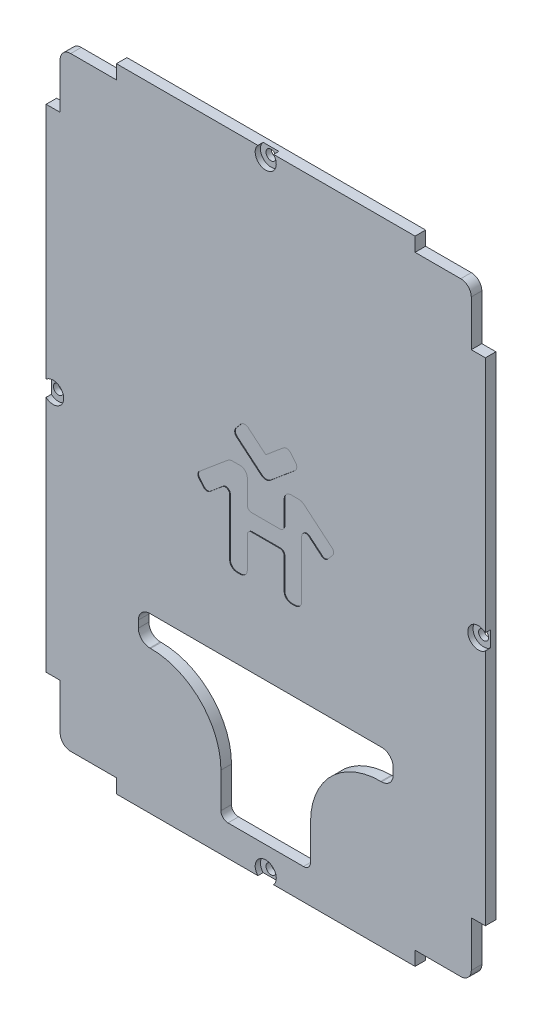
SolidWorks part; units mm, degrees
ref_plane "Спереди" through (0, 0, 0) normal (0, 0, 1) x (1, 0, 0)
ref_plane "Сверху" through (0, 0, 0) normal (0, 1, 0) x (1, 0, 0)
ref_plane "Справа" through (0, 0, 0) normal (1, 0, 0) x (0, 0, -1)
sketch "Эскиз1" plane through (0, 0, 0) normal (0, 0, 1) x (1, 0, 0)
  line L1 (-52.5, -90) -> (52.5, -90)
  line L2 (-62.5, -80) -> (-62.5, 80)
  line L3 (-52.5, 90) -> (52.5, 90)
  line L4 (62.5, -80) -> (62.5, 80)
  line L5 (-62.5, -90) -> (62.5, 90) construction
  line L6 (-62.5, 90) -> (62.5, -90) construction
  arc A0 (-52.5, 90) -> (-62.5, 80) centre (-52.5, 80) ccw
  arc A1 (-52.5, -90) -> (-62.5, -80) centre (-52.5, -80) cw
  arc A2 (52.5, 90) -> (62.5, 80) centre (52.5, 80) cw
  arc A3 (62.5, -80) -> (52.5, -90) centre (52.5, -80) cw
  point P0 (0, 0)
  dimension "D3" = 10
  dimension "D4" = 10
  dimension "D1" = 125
  dimension "D2" = 180
extrude "Бобышка-Вытянуть1" add sketch "Эскиз1" along normal blind 3
sketch "Эскиз2" plane through (0, 0, 0) normal (0, 0, -1) x (-1, 0, 0)
  line L0 (-36.25, -44) -> (-36.25, -46)
  line L1 (-33, -49.25) -> (-32.75, -49.25)
  line L2 (-12.75, -69.25) -> (-12.75, -79.25)
  line L3 (-10.75, -81.25) -> (10.75, -81.25)
  line L4 (12.75, -79.25) -> (12.75, -69.25)
  line L5 (32.75, -49.25) -> (33, -49.25)
  line L6 (36.25, -46) -> (36.25, -44)
  line L7 (33, -40.75) -> (-33, -40.75)
  line L8 (-62.5, -80) -> (-62.5, 80) construction
  line L9 (62.5, 80) -> (62.5, -80) construction
  line L10 (52.5, -90) -> (-52.5, -90) construction
  arc A0 (32.75, -49.25) -> (12.75, -69.25) centre (32.75, -69.25) ccw
  arc A1 (-12.75, -69.25) -> (-32.75, -49.25) centre (-32.75, -69.25) ccw
  arc A2 (33, -49.25) -> (36.25, -46) centre (33, -46) ccw
  arc A3 (36.25, -44) -> (33, -40.75) centre (33, -44) ccw
  arc A4 (-33, -49.25) -> (-36.25, -46) centre (-33, -46) cw
  arc A5 (-33, -40.75) -> (-36.25, -44) centre (-33, -44) ccw
  arc A6 (12.75, -79.25) -> (10.75, -81.25) centre (10.75, -79.25) cw
  arc A7 (-10.75, -81.25) -> (-12.75, -79.25) centre (-10.75, -79.25) cw
  point P16 (12.75, -49.25)
  point P21 (36.25, -49.25)
  point P24 (36.25, -40.75)
  point P31 (12.75, -81.25)
  point P34 (-12.75, -81.25)
  dimension "D7" = 20
  dimension "D8" = 3.25
  dimension "D9" = 2
  dimension "D1" = 26.25
  dimension "D2" = 26.25
  dimension "D3" = 49.25
  dimension "D4" = 8.5
  dimension "D5" = 25.5
  dimension "D6" = 32
extrude "Вырез-Вытянуть1" cut sketch "Эскиз2" against normal blind 10
sketch "Эскиз3" plane through (0, 0, 3) normal (0, 0, 1) x (1, 0, 0)
  line L0 (-60.5, -940.9285) -> (-60.5, 49059.0715) construction
  line L1 (60.5, -944.6511) -> (60.5, 49055.3489) construction
  line L2 (-1032.3277, 88) -> (48967.6723, 88) construction
  line L3 (-1028.801, -88) -> (48971.199, -88) construction
  line L4 (-52.5, -90) -> (52.5, -90) construction
  line L6 (-62.5, 80) -> (-62.5, -80) construction
  line L7 (62.5, -80) -> (62.5, 80) construction
  line L8 (52.5, 90) -> (-52.5, 90) construction
  line L9 (0, -925) -> (0, 49075) construction
  line L10 (-1052.5, 0) -> (48947.5, 0) construction
  circle A1 centre (0, 88) radius 3
  circle A3 centre (60.5, 0) radius 3
  circle A5 centre (0, -88) radius 3
  circle A7 centre (-60.5, 0) radius 3
  point P19 (0, 90)
  point P22 (-62.5, 0)
  dimension "D5" = 6
  dimension "D1" = 2
  dimension "D2" = 2
  dimension "D3" = 2
  dimension "D4" = 2
extrude "Вырез-Вытянуть2" cut sketch "Эскиз3" against normal blind 1.5
sketch "Эскиз4" plane through (0, 0, 1.5) normal (0, 0, 1) x (1, 0, 0)
  circle A1 centre (0, 88) radius 1.425
  circle A3 centre (60.5, 0) radius 1.425
  circle A5 centre (0, -88) radius 1.425
  circle A7 centre (-60.5, 0) radius 1.425
  dimension "D1" = 2.85
extrude "Вырез-Вытянуть3" cut sketch "Эскиз4" against normal blind 2
sketch "Эскиз5" plane through (0, 0, 3) normal (0, 0, 1) x (1, 0, 0)
  line L0 (-10.25, -0.0911) -> (-10.25, -16.2185)
  line L1 (-8.25, -18.2185) -> (-7.25, -18.2185)
  line L2 (-5.25, -16.2185) -> (-5.25, -7.4685)
  line L3 (-4, -6.2185) -> (4, -6.2185)
  line L4 (-9.3401, 8.5815) -> (-7.25, 8.5815)
  line L5 (-5.25, 6.5815) -> (-5.25, -0.1685)
  line L6 (0, -1000.6685) -> (0, 48999.3315) construction
  line L7 (-4, -1.4185) -> (4, -1.4185)
  line L8 (-10.947, 7.9966) -> (-18.868, 1.3501)
  line L9 (-19.0221, -0.4109) -> (-17.6786, -2.012)
  line L10 (-15.9176, -2.1661) -> (-12.3035, 0.8665)
  line L11 (15.9176, -2.1661) -> (12.3035, 0.8665)
  line L12 (19.0221, -0.4109) -> (17.6786, -2.012)
  line L13 (10.947, 7.9966) -> (18.868, 1.3501)
  line L14 (5.25, 6.5815) -> (5.25, -0.1685)
  line L15 (9.3401, 8.5815) -> (7.25, 8.5815)
  line L16 (5.25, -16.2185) -> (5.25, -7.4685)
  line L17 (8.25, -18.2185) -> (7.25, -18.2185)
  line L18 (10.25, -0.0911) -> (10.25, -16.2185)
  line L19 (0, 14.8585) -> (-4.9795, 19.0368)
  line L20 (-7.0927, 18.8519) -> (-8.4839, 17.194)
  line L21 (-8.299, 15.0808) -> (-1.2856, 9.1958)
  line L22 (8.299, 15.0808) -> (1.2856, 9.1958)
  line L23 (0, 14.8585) -> (4.9795, 19.0368)
  line L24 (7.0927, 18.8519) -> (8.4839, 17.194)
  arc A0 (-10.25, -16.2185) -> (-8.25, -18.2185) centre (-8.25, -16.2185) ccw
  arc A1 (-7.25, -18.2185) -> (-5.25, -16.2185) centre (-7.25, -16.2185) ccw
  arc A2 (-5.25, 6.5815) -> (-7.25, 8.5815) centre (-7.25, 6.5815) ccw
  arc A3 (-9.3401, 8.5815) -> (-10.947, 7.9966) centre (-9.3401, 6.0815) ccw
  arc A4 (-4, -6.2185) -> (-5.25, -7.4685) centre (-4, -7.4685) ccw
  arc A5 (-4, -1.4185) -> (-5.25, -0.1685) centre (-4, -0.1685) cw
  arc A6 (-10.25, -0.0911) -> (-12.3035, 0.8665) centre (-11.5, -0.0911) ccw
  arc A7 (-15.9176, -2.1661) -> (-17.6786, -2.012) centre (-16.721, -1.2085) cw
  arc A8 (-18.868, 1.3501) -> (-19.0221, -0.4109) centre (-18.0645, 0.3926) ccw
  arc A9 (18.868, 1.3501) -> (19.0221, -0.4109) centre (18.0645, 0.3926) cw
  arc A10 (15.9176, -2.1661) -> (17.6786, -2.012) centre (16.721, -1.2085) ccw
  arc A11 (10.25, -0.0911) -> (12.3035, 0.8665) centre (11.5, -0.0911) cw
  arc A12 (4, -1.4185) -> (5.25, -0.1685) centre (4, -0.1685) ccw
  arc A13 (4, -6.2185) -> (5.25, -7.4685) centre (4, -7.4685) cw
  arc A14 (9.3401, 8.5815) -> (10.947, 7.9966) centre (9.3401, 6.0815) cw
  arc A15 (5.25, 6.5815) -> (7.25, 8.5815) centre (7.25, 6.5815) cw
  arc A16 (7.25, -18.2185) -> (5.25, -16.2185) centre (7.25, -16.2185) cw
  arc A17 (10.25, -16.2185) -> (8.25, -18.2185) centre (8.25, -16.2185) cw
  arc A18 (-8.299, 15.0808) -> (-8.4839, 17.194) centre (-7.3348, 16.2298) cw
  arc A19 (-4.9795, 19.0368) -> (-7.0927, 18.8519) centre (-5.9437, 17.8877) ccw
  arc A20 (4.9795, 19.0368) -> (7.0927, 18.8519) centre (5.9437, 17.8877) cw
  arc A21 (8.299, 15.0808) -> (8.4839, 17.194) centre (7.3348, 16.2298) ccw
  arc A22 (1.2856, 9.1958) -> (-1.2856, 9.1958) centre (0, 10.7279) cw
  point P35 (0, -6.2185)
  point P36 (0, -1.4185)
  point P61 (19.57, 0.5466)
  point P62 (4.9945, -1.4185)
  point P63 (4.9945, -6.2185)
  point P64 (9.9945, 8.5815)
  point P65 (4.9945, 8.5815)
  point P66 (4.9945, -18.2185)
  point P67 (9.9945, -18.2185)
  point P79 (5.7231, 19.8752)
  point P80 (8.937, 16.0449)
  dimension "D3" = 2
  dimension "D4" = 2.5
  dimension "D6" = 1.5
  dimension "D7" = 2
  dimension "D8" = 1.25
  dimension "D1" = 5.25
  dimension "D2" = 50
  dimension "D5" = 50
extrude "Вырез-Вытянуть4" cut sketch "Эскиз5" against normal blind 0.2
sketch "Эскиз8" plane through (0, 0, 3) normal (0, 0, 1) x (1, 0, 0)
  line L0 (-52.5, 90) -> (-42.5, 90)
  line L1 (-2.2361, 90) -> (-52.5, 90) construction
  line L2 (-42.5, 90) -> (-42.5, 86)
  line L3 (-42.5, 86) -> (-55.5, 86)
  line L5 (-58.5, 83) -> (-58.5, 70)
  line L6 (-58.5, 70) -> (-62.5, 70)
  line L7 (-62.5, 80) -> (-62.5, 2.2361) construction
  line L8 (-62.5, 70) -> (-62.5, 80)
  line L9 (-1000, 0) -> (49000, 0) construction
  line L10 (0, -1000) -> (0, 49000) construction
  line L11 (62.5, 70) -> (62.5, 80)
  line L12 (58.5, 70) -> (62.5, 70)
  line L13 (58.5, 83) -> (58.5, 70)
  line L14 (42.5, 86) -> (55.5, 86)
  line L15 (42.5, 90) -> (42.5, 86)
  line L16 (52.5, 90) -> (42.5, 90)
  line L17 (52.5, -90) -> (42.5, -90)
  line L18 (42.5, -90) -> (42.5, -86)
  line L19 (42.5, -86) -> (55.5, -86)
  line L20 (58.5, -83) -> (58.5, -70)
  line L21 (58.5, -70) -> (62.5, -70)
  line L22 (62.5, -70) -> (62.5, -80)
  line L23 (-62.5, -70) -> (-62.5, -80)
  line L24 (-58.5, -70) -> (-62.5, -70)
  line L25 (-58.5, -83) -> (-58.5, -70)
  line L26 (-42.5, -86) -> (-55.5, -86)
  line L27 (-42.5, -90) -> (-42.5, -86)
  line L28 (-52.5, -90) -> (-42.5, -90)
  arc A0 (-52.5, 90) -> (-62.5, 80) centre (-52.5, 80) ccw construction
  arc A1 (-52.5, 90) -> (-62.5, 80) centre (-52.5, 80) ccw
  arc A2 (-58.5, 83) -> (-55.5, 86) centre (-55.5, 83) cw
  arc A3 (58.5, 83) -> (55.5, 86) centre (55.5, 83) ccw
  arc A4 (52.5, 90) -> (62.5, 80) centre (52.5, 80) cw
  arc A5 (52.5, -90) -> (62.5, -80) centre (52.5, -80) ccw
  arc A6 (58.5, -83) -> (55.5, -86) centre (55.5, -83) cw
  arc A7 (-58.5, -83) -> (-55.5, -86) centre (-55.5, -83) ccw
  arc A8 (-52.5, -90) -> (-62.5, -80) centre (-52.5, -80) cw
  dimension "D3" = 3
  dimension "D1" = 10
  dimension "D2" = 4
extrude "Вырез-Вытянуть5" cut sketch "Эскиз8" against normal blind 10
